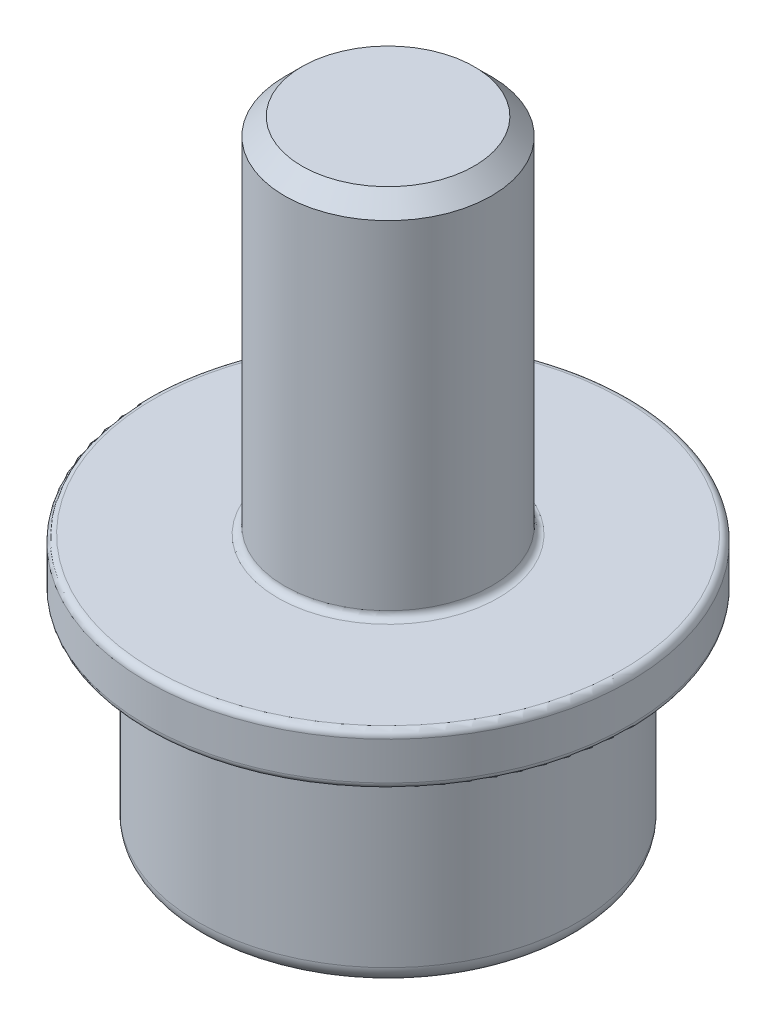
SolidWorks part; units mm, degrees
ref_plane "Front Plane" through (0, 0, 0) normal (0, 0, 1) x (1, 0, 0)
ref_plane "Top Plane" through (0, 0, 0) normal (0, 1, 0) x (1, 0, 0)
ref_plane "Right Plane" through (0, 0, 0) normal (1, 0, 0) x (0, 0, -1)
sketch "Sketch1" plane through (0, 0, 0) normal (0, 1, 0) x (1, 0, 0)
  circle A0 centre (0, 0) radius 2.75
  dimension "D1" = 5.5
extrude "Boss-Extrude1" add sketch "Sketch1" along normal blind 3
sketch "Sketch2" plane through (0, 3, 0) normal (0, 1, 0) x (1, 0, 0)
  circle A0 centre (0, 0) radius 1.5
  dimension "D1" = 3
extrude "Boss-Extrude2" add sketch "Sketch2" along normal blind 6 contours A0
sketch "Sketch3" plane through (0, 0, 0) normal (0, -1, 0) x (1, 0, 0)
  line L1 (0.9342, 0.9746) -> (-0.3769, 1.2963)
  line L2 (-0.3769, 1.2963) -> (-1.3111, 0.3217)
  line L3 (-1.3111, 0.3217) -> (-0.9342, -0.9746)
  line L4 (-0.9342, -0.9746) -> (0.3769, -1.2963)
  line L5 (0.3769, -1.2963) -> (1.3111, -0.3217)
  line L6 (1.3111, -0.3217) -> (0.9342, 0.9746)
  circle A0 centre (0, 0) radius 1.1691 construction
  dimension "D1" = 2.7
extrude "Cut-Extrude1" cut sketch "Sketch3" against normal blind 1.5
chamfer "Chamfer1" distance 0.25 distance2 0.25 6 edges at (-0.2786, 0, -1.1355) (-1.1226, 0, -0.3264) (-0.844, 0, 0.809) (0.2786, 0, 1.1355) (1.1226, 0, 0.3264) (0.844, 0, -0.809)
fillet "Fillet1" radius 0.25 1 edges at (0, 0, 2.75)
chamfer "Chamfer2" distance 0.25 angle 45 1 edges at (0, 9, 1.5)
fillet "Fillet2" radius 0.1 1 edges at (0, 3, 2.75)
sketch "Sketch4" plane through (0, 3, 0) normal (0, 1, 0) x (1, 0, 0)
  circle A0 centre (0, 0) radius 1.5
  circle A1 centre (0, 0) radius 3.5
  circle A2 centre (0, 0) radius 1.5 construction
  dimension "D1" = 7
extrude "Boss-Extrude3" add sketch "Sketch4" along normal blind 0.75
fillet "Fillet3" radius 0.1 3 edges at (0, 3.75, 1.5) (0, 3.75, 3.5) (0, 3, 3.5)
